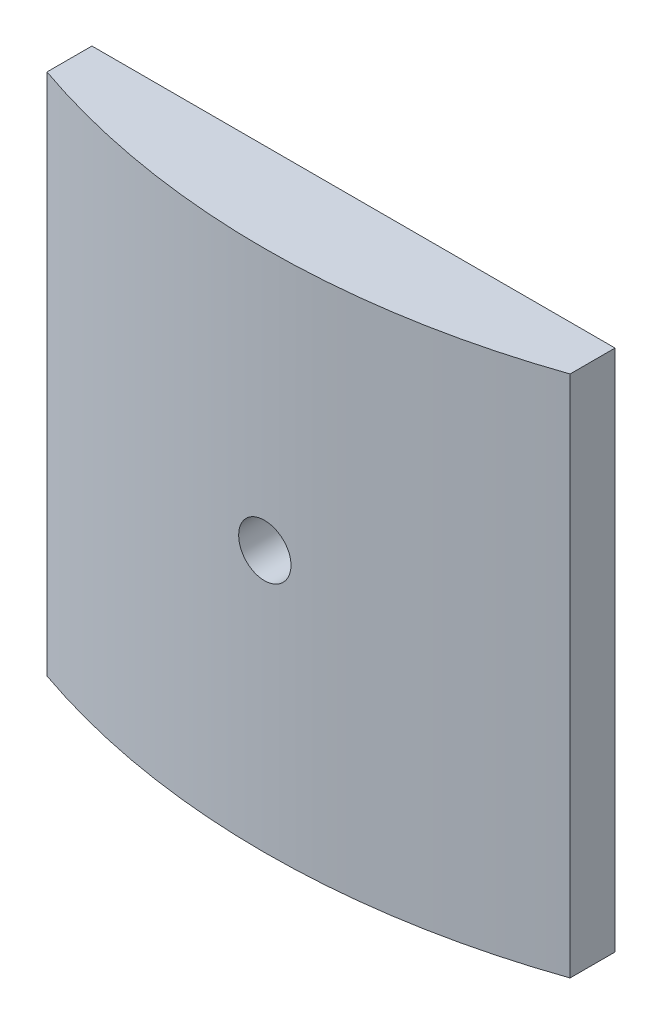
SolidWorks part; units mm, degrees
material "ABS"
ref_plane "Front Plane" through (0, 0, 0) normal (0, 0, 1) x (1, 0, 0)
ref_plane "Top Plane" through (0, 0, 0) normal (0, 1, 0) x (1, 0, 0)
ref_plane "Right Plane" through (0, 0, 0) normal (1, 0, 0) x (0, 0, -1)
sketch "Sketch2" plane through (0, 0, 0) normal (0, 1, 0) x (1, 0, 0)
  line L1 (-17.5, -33.8432) -> (17.5, -33.8432) construction
  line L2 (0, 0) -> (0, -60.5871) construction
  line L3 (0, -33.8432) -> (-12.5, -33.8432)
  line L4 (0, -33.8432) -> (12.5, -33.8432)
  line L7 (-12.5, -33.8432) -> (-12.5, -35.9911)
  line L8 (12.5, -33.8432) -> (12.5, -35.9911)
  circle A2 centre (0, 0) radius 38.1 construction
  arc A3 (-12.5, -35.9911) -> (12.5, -35.9911) centre (0, 0) ccw
  point P11 (0, -38.1)
  point P12 (0, -33.8432)
  dimension "D5" = 76.2
  dimension "D2" = 35
  dimension "D3" = 12.5
  dimension "D4" = 12.5
extrude "Boss-Extrude1" add sketch "Sketch2" along normal blind 25 contours L3 L7 A3 L8 L4
sketch "Sketch3" plane through (0, 0, 33.8432) normal (0, 0, -1) x (-1, 0, 0)
  line L0 (-12.5, 0) -> (12.5, 25) construction
  line L1 (-12.5, 25) -> (12.5, 0) construction
  circle A0 centre (0, 12.5) radius 1.25
  dimension "D1" = 2.5
extrude "Cut-Extrude1" cut sketch "Sketch3" against normal blind 20
